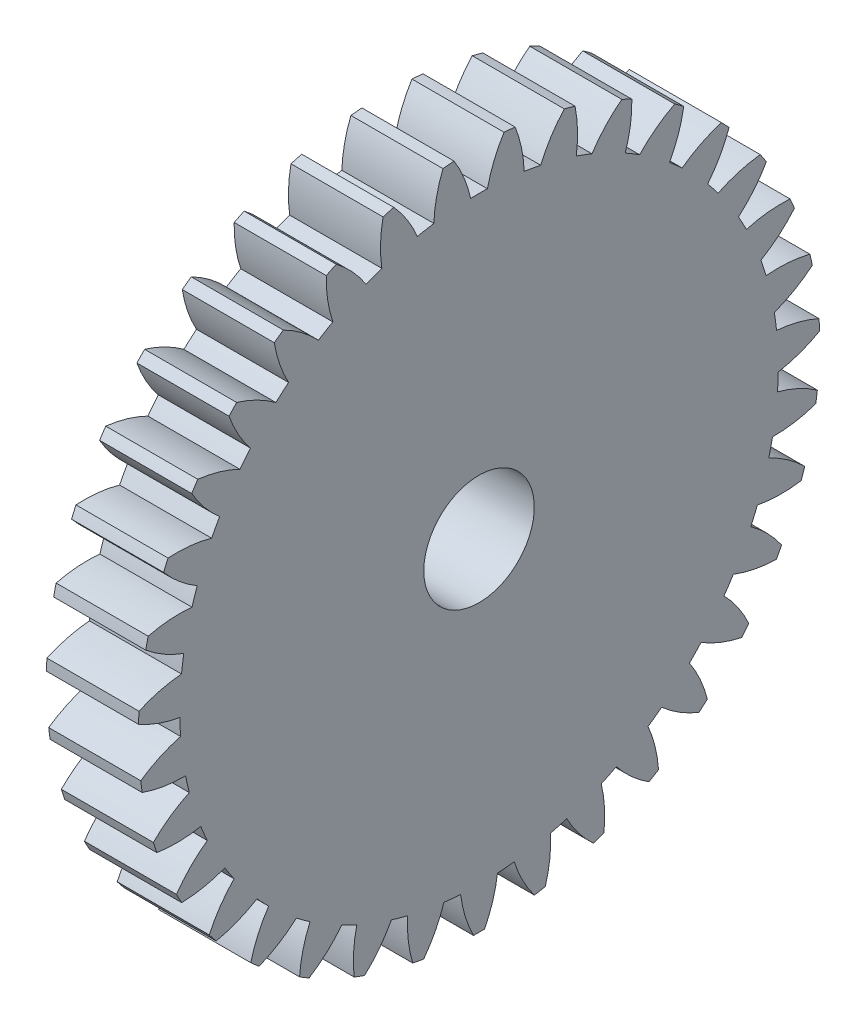
SolidWorks part; units mm, degrees
ref_plane "Plane1" through (0, 0, 0) normal (0, 0, 1) x (1, 0, 0)
ref_plane "Plane2" through (0, 0, 0) normal (0, 1, 0) x (1, 0, 0)
ref_plane "Plane3" through (0, 0, 0) normal (1, 0, 0) x (0, 0, -1)
sketch "HoldingSke" plane through (0, 0, 0) normal (0, 1, 0) x (1, 0, 0)
  line L0 (0, 0) -> (0.8192, -0.5736)
  line L1 (-15, 0) -> (100, 0) construction
  line L2 (0, 0) -> (-2.1039, 2.3779)
  line L3 (0, 0) -> (-11.863, 4.5341)
  line L4 (0, 0) -> (7.0742, 4.9534)
  line L5 (0, 0) -> (-10.3065, -3.844)
  line L6 (0, 0) -> (-4.1448, -2.7965)
  line L7 (-2.1039, 2.3779) -> (0.2639, 13.1201)
  line L8 (-76.2, 54.61) -> (-75.2, 54.61)
  line L9 (-71.009, 38.7566) -> (-53.1078, 45.2721)
  line L10 (-76.2, 71.12) -> (104.1128, 71.12)
  line L11 (0, 0) -> (-5, 0)
  line L12 (-76.2, 101.6) -> (-76.162, 101.6)
  line L13 (24.9733, 27.94) -> (52.9518, 28.4284)
  line L14 (24.9733, 27.94) -> (24.9743, 27.94)
  line L15 (24.9733, 27.94) -> (100.4006, 29.5858)
  line L16 (-63.627, -1) -> (-12.827, -1)
  circle A0 centre (0, 0) radius 3
  circle A1 centre (0, 0) radius 7
  circle A2 centre (0, 0) radius 7
  circle A3 centre (0, 0) radius 3
  dimension "MHD" = 14
  dimension "Hub_dia" = 14
  dimension "Bore" = 6
  dimension "MBD" = 6
  dimension "Num_teeth" = 35
  dimension "Pitch" = 1
  dimension "Overall_len" = 11
  dimension "Show_teeth" = 35
  dimension "Thickness" = 5
  dimension "OAL" = 11.0001
  dimension "T_dim" = 1
  dimension "Ap" = 20
  dimension "H" = 19.05
  dimension "Pitch_radius" = 180.3128
  dimension "Width" = 5
  dimension "Backlash" = 0.038
  dimension "Addendum_fac" = 1
  dimension "Dedendum_fac" = 1.25
  dimension "Clearance_fac" = 0.25
  dimension "Dedendum_add" = 0.001
  dimension "Module" = 1
sketch "BasProSke" plane through (0, 0, 0) normal (0, 1, 0) x (1, 0, 0)
  line L0 (-10, 0) -> (60, 0) construction
  line L1 (0, 0) -> (0, 18.5)
  line L2 (0, 0) -> (5, 0)
  line L3 (5, 0) -> (5, 18.5)
  line L4 (5, 18.5) -> (0, 18.5)
  dimension "Thickness" = 5
  dimension "Diameter" = 37
revolve "Base-Revolve" add sketch "BasProSke" angle 360 about L0
sketch "TooCutSke" plane through (0, 0, 0) normal (1, 0, 0) x (0, 0, -1)
  line L1 (0, 0) -> (0, 107) construction
  line L2 (0, 0) -> (-0.8516, 17.4793) construction
  line L3 (0, 0) -> (-3.1347, 34.8297) construction
  line L4 (-0.8516, 17.4793) -> (-1.5674, 17.4148) construction
  arc A0 (0.4564, 16.2426) -> (-0.4564, 16.2426) centre (0, 0) ccw
  arc A1 (1.373, 18.4745) -> (-1.373, 18.4745) centre (0, 0) ccw
  circle A2 centre (0, 0) radius 17.5 construction
  circle A3 centre (0, 0) radius 16.4446 construction
  arc A4 (-0.4564, 16.2426) -> (-1.373, 18.4745) centre (-7.293, 14.739) ccw
  arc A5 (1.373, 18.4745) -> (0.4564, 16.2426) centre (7.293, 14.739) ccw
  dimension "Root_dia" = 32.498
  dimension "Overcut_dia" = 37.0508
  dimension "Pitch_dia" = 35
  dimension "Base_dia" = 32.8892
  dimension "Flank_rad" = 7
  dimension "Half_ang" = 5.143
  dimension "Half_CT" = 0.7186
extrude "ToothCut" cut sketch "TooCutSke" along normal through all
fillet "Breaks" [suppressed] radius 0.02
fillet "RootFillets" [suppressed] radius 0.251
pattern_circular "TeethCuts" count 35 every 10.286 about axis through (-10, 0, 0) along (1, 0, 0) of "ToothCut", "RootFillets", "Breaks"
sketch "HubNeaOneSke" plane through (0, 0, 0) normal (-1, 0, 0) x (0, 0, 1)
  circle A0 centre (0, 0) radius 7
  dimension "Diameter" = 14
extrude "HubNearOne" add sketch "HubNeaOneSke" along normal blind 6.0001
sketch "HubNeaBotSke" plane through (0, 0, 0) normal (-1, 0, 0) x (0, 0, 1)
  circle A0 centre (0, 0) radius 7
  dimension "Diameter" = 14
extrude "HubNearBoth" [suppressed] add sketch "HubNeaBotSke" along normal blind 3
ref_plane "FarPln" through (5, 0, 0) normal (1, 0, 0) x (0, 0, -1)
sketch "HubFarSke" plane through (5, 0, 0) normal (1, 0, 0) x (0, 0, -1)
  circle A0 centre (0, 0) radius 7
  dimension "Diameter" = 14
extrude "HubFar" [suppressed] add sketch "HubFarSke" along normal blind 3
sketch "BorSke" plane through (0, 0, 0) normal (1, 0, 0) x (0, 0, -1)
  circle A0 centre (0, 0) radius 3
  dimension "Diameter" = 6
extrude "Bore" cut sketch "BorSke" along normal mid plane 22.0001
sketch "KeySke" plane through (0, 0, 0) normal (1, 0, 0) x (0, 0, -1)
  line L0 (-1, 0) -> (-1, 4)
  line L1 (-1, 4) -> (1, 4)
  line L2 (1, 4) -> (1, 0)
  line L3 (0, 0) -> (0, 34) construction
  line L4 (-1, 0) -> (1, 0)
  dimension "Offset" = 4
  dimension "Width" = 2
extrude "Keyway" [suppressed] cut sketch "KeySke" along normal mid plane 22.0001
pattern_circular "Keyway2" [suppressed] count 2 every 90 about axis through (-10, 0, 0) along (1, 0, 0)
equation "' \"Module@HoldingSke\" = 6.35"
equation "' \"Num_teeth@HoldingSke\" = 12"
equation "' \"Ap@HoldingSke\" =  20"
equation "' \"Ap@HoldingSke\" = 20"
equation "' \"Width@HoldingSke\" = 0.5 * 25.4"
equation "' \"Hub_dia@HoldingSke\"= 1 * 25.4"
equation "' \"Hub_dia@HoldingSke\" = 1 * 25.4"
equation "' \"Overall_len@HoldingSke\" = 1.0 * 25.4"
equation "' \"Bore@HoldingSke\" = 0.75 * 25.4"
equation "' \"T_dim@HoldingSke\" = 0.1 * 25.4"
equation "' \"Width@KeySke\" = 0.25 * 25.4"
equation "' \"Show_teeth@HoldingSke\" = 13"
equation "' \"Backlash@HoldingSke\" = 0.009 * 25.4"
equation "' \"Addendum_fac@HoldingSke\" = 1.0"
equation "' \"Dedendum_fac@HoldingSke\" = 1.25"
equation "' \"Dedendum_add@HoldingSke\" = 0.00005 * 25.4"
equation "' \"Clearance_fac@HoldingSke\" = 0.25"
equation "\"Pitch@HoldingSke\" = 1 / \"Module@HoldingSke\""
equation "\"Overcut_dia@TooCutSke\" = (\"Num_teeth@HoldingSke\" + 2 * \"Addendum_fac@HoldingSke\") / \"Pitch@HoldingSke\" + 0.002 * 25.4"
equation "\"Pitch_dia@TooCutSke\" = \"Num_teeth@HoldingSke\" / \"Pitch@HoldingSke\""
equation "\"Base_dia@TooCutSke\" = \"Num_teeth@HoldingSke\" / \"Pitch@HoldingSke\" * cos((\"Ap@HoldingSke\"  * 3.14159265 / 180))"
equation "\"Root_dia@TooCutSke\" = (\"Num_teeth@HoldingSke\" + 2) / \"Pitch@HoldingSke\" - 2 * (\"Addendum_fac@HoldingSke\" + \"Dedendum_fac@HoldingSke\") / \"Pitch@HoldingSke\" - \"Dedendum_add@HoldingSke\" * 2"
equation "\"Half_ang@TooCutSke\" = 180 / \"Num_teeth@HoldingSke\""
equation "\"Half_CT@TooCutSke\" = \"Num_teeth@HoldingSke\" / \"Pitch@HoldingSke\" * sin((3.14159265 / 2 / \"Num_teeth@HoldingSke\")) / 2 - 7 * \"Backlash@HoldingSke\" / 4"
equation "\"Flank_rad@TooCutSke\" = \"Num_teeth@HoldingSke\" / \"Pitch@HoldingSke\" / 5"
equation "\"Radius@RootFillets\" = \"Clearance_fac@HoldingSke\" / \"Pitch@HoldingSke\" + \"Dedendum_add@HoldingSke\""
equation "\"Break_rad@Breaks\" = 0.02 / \"Pitch@HoldingSke\""
equation "\"Thickness@HoldingSke\" = \"Width@HoldingSke\""
equation "\"OAL@HoldingSke\" = \"Thickness@HoldingSke\""
equation "\"MHD@HoldingSke\" = (\"Num_teeth@HoldingSke\" + 2) / \"Pitch@HoldingSke\" - 2 * (\"Addendum_fac@HoldingSke\" + \"Dedendum_fac@HoldingSke\")  / \"Pitch@HoldingSke\" - \"Dedendum_add@HoldingSke\" * 2"
equation "\"MBD@HoldingSke\" = (\"Num_teeth@HoldingSke\" + 2) / \"Pitch@HoldingSke\" - 2 * (\"Addendum_fac@HoldingSke\" + \"Dedendum_fac@HoldingSke\")  / \"Pitch@HoldingSke\" - \"Dedendum_add@HoldingSke\" * 2 - 0.002 * 25.4"
equation "\"MHD@HoldingSke\" = ((sgn( \"MHD@HoldingSke\" - \"Hub_dia@HoldingSke\" )-1)*( \"MHD@HoldingSke\" - \"Hub_dia@HoldingSke\" ))/-2+ \"Hub_dia@HoldingSke\""
equation "\"MBD@HoldingSke\" = ((sgn( \"MBD@HoldingSke\" - \"Bore@HoldingSke\" )-1)*( \"MBD@HoldingSke\" - \"Bore@HoldingSke\" ))/-2+ \"Bore@HoldingSke\""
equation "\"OAL@HoldingSke\" = ((sgn( \"OAL@HoldingSke\" - \"Overall_len@HoldingSke\" )+1)*( \"OAL@HoldingSke\" - \"Overall_len@HoldingSke\" ))/2 + \"Overall_len@HoldingSke\" + 0.000002 * 25.4"
equation "\"Num_teeth@TeethCuts\" = int( \"Show_teeth@HoldingSke\" ) + 1"
equation "\"Num_teeth@TeethCuts\" = ((sgn( \"Num_teeth@TeethCuts\" - \"Num_teeth@HoldingSke\" )-1)*( \"Num_teeth@TeethCuts\" - \"Num_teeth@HoldingSke\" ))/-2+ \"Num_teeth@HoldingSke\""
equation "\"Num_teeth@TeethCuts\" = ((sgn( \"Num_teeth@TeethCuts\" - 2.0)+1)*( \"Num_teeth@TeethCuts\" - 2.0))/2 +2.0"
equation "\"Angle@TeethCuts\" = 360.0 / \"Num_teeth@HoldingSke\""
equation "\"Diameter@BasProSke\" = (\"Num_teeth@HoldingSke\" + 2 * \"Addendum_fac@HoldingSke\") / \"Pitch@HoldingSke\""
equation "\"Thickness@BasProSke\"  = \"Thickness@HoldingSke\""
equation "' \"Fillet_rad@BasProSke\" =  \"Thickness@HoldingSke\" * 0.05"
equation "' \"Fillet_rad@BasProSke\" = \"Thickness@HoldingSke\" * 0.05"
equation "\"MHD@HoldingSke\" = ((sgn( \"MHD@HoldingSke\" - \"Root_dia@TooCutSke\" )-1)*( \"MHD@HoldingSke\" - \"Root_dia@TooCutSke\" ))/-2+ \"Root_dia@TooCutSke\""
equation "\"Diameter@HubNeaOneSke\" = \"MHD@HoldingSke\""
equation "\"Length@HubNearOne\" = \"OAL@HoldingSke\" - \"Thickness@BasProSke\""
equation "\"Diameter@HubNeaBotSke\" = \"MHD@HoldingSke\""
equation "\"Length@HubNearBoth\" = ( \"OAL@HoldingSke\" - \"Thickness@BasProSke\" ) / 2.0"
equation "\"Thickness@FarPln\" = \"Thickness@BasProSke\""
equation "\"Diameter@HubFarSke\" = \"MHD@HoldingSke\""
equation "\"Length@HubFar\" = ( \"OAL@HoldingSke\" - \"Thickness@BasProSke\" ) / 2.0"
equation "\"Diameter@BorSke\" = \"MBD@HoldingSke\""
equation "\"D1@Bore\" = \"OAL@HoldingSke\" * 2.0"
equation "\"D1@Keyway\" = \"OAL@HoldingSke\" * 2.0"
equation "\"Offset@KeySke\" = \"T_dim@HoldingSke\" + \"MBD@HoldingSke\" / 2.0"
